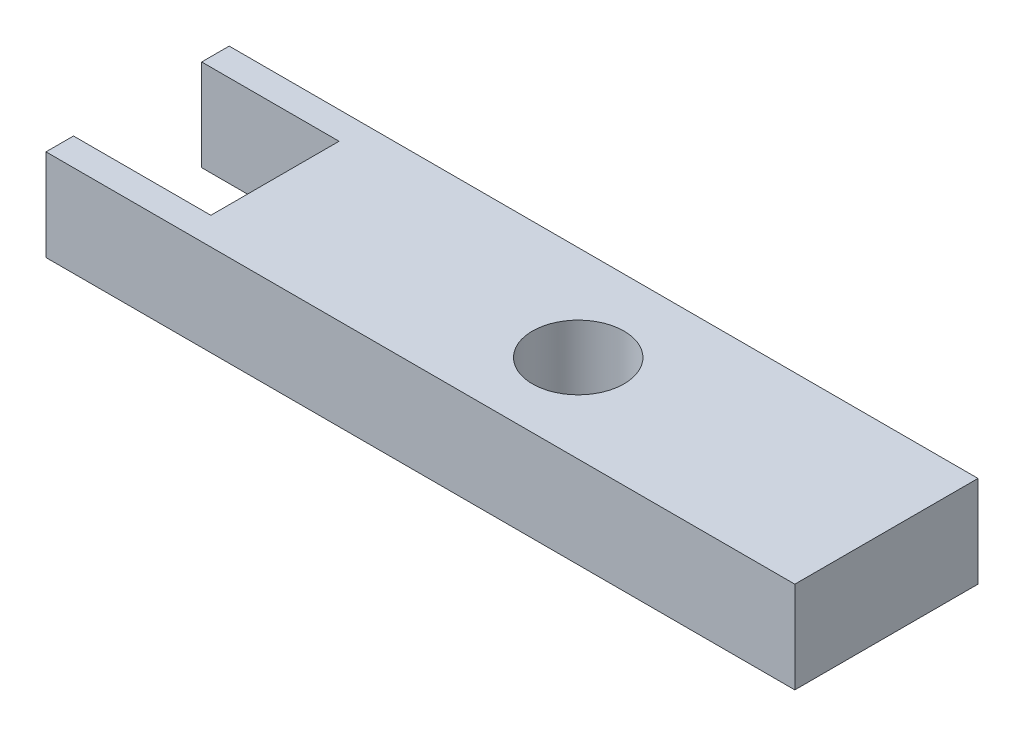
SolidWorks part; units mm, degrees
ref_plane "Front Plane" through (0, 0, 0) normal (0, 0, 1) x (1, 0, 0)
ref_plane "Top Plane" through (0, 0, 0) normal (0, 1, 0) x (1, 0, 0)
ref_plane "Right Plane" through (0, 0, 0) normal (1, 0, 0) x (0, 0, -1)
sketch "Sketch1" plane through (0, 0, 0) normal (0, 1, 0) x (1, 0, 0)
  line L0 (0, 0) -> (58.42, 0)
  line L1 (58.42, 0) -> (58.42, -10.16)
  line L2 (58.42, -10.16) -> (0, -10.16)
  line L6 (0, -10.16) -> (0, 0)
  dimension "D1" = 10.16
  dimension "D2" = 58.42
extrude "Boss-Extrude2" add sketch "Sketch1" along normal blind 5.08
sketch "Sketch2" plane through (0, 0, 0) normal (0, 1, 0) x (1, 0, 0)
  line L0 (0, 0) -> (0, -10.16) construction
  line L1 (0, -1.524) -> (24.5047, -1.524)
  line L2 (0, -1.524) -> (0, -8.636)
  line L3 (0, -8.636) -> (24.5047, -8.636)
  line L5 (58.42, -10.16) -> (58.42, 0) construction
  line L6 (24.5047, -1.524) -> (24.5047, -8.636)
  point P8 (0, -5.08)
  point P10 (58.42, -5.08)
  dimension "D1" = 3.556
  dimension "D2" = 24.5047
  dimension "D3" = 1.524
extrude "Cut-Extrude1" cut sketch "Sketch2" along normal blind 11.938
sketch "Sketch3" plane through (0, 0, 0) normal (0, 1, 0) x (1, 0, 0)
  line L0 (24.5047, -8.636) -> (24.5047, -1.524) construction
  line L1 (-0.0904, 5.8435) -> (16.8847, 5.8435)
  line L2 (-0.0904, 5.8435) -> (-0.0904, -12.3496)
  line L3 (-0.0904, -12.3496) -> (16.8847, -12.3496)
  line L4 (16.8847, 5.8435) -> (16.8847, -12.3496)
  dimension "D1" = 7.62
  dimension "D2" = 0.0904
  dimension "D3" = 5.8435
  dimension "D4" = 12.3496
extrude "Cut-Extrude2" cut sketch "Sketch3" along normal blind 11.938
sketch "Sketch4" plane through (0, 0, 0) normal (0, 1, 0) x (1, 0, 0)
  circle A0 centre (41.5227, -5.2784) radius 2.54
  dimension "D1" = 5.08
extrude "Cut-Extrude3" cut sketch "Sketch4" along normal blind 8.382
